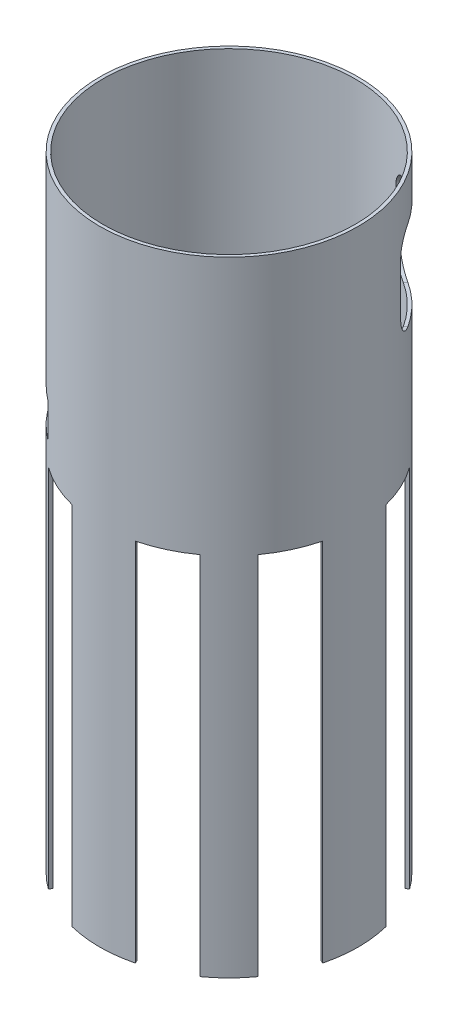
SolidWorks part; units mm, degrees
ref_plane "Front Plane" through (0, 0, 0) normal (0, 0, 1) x (1, 0, 0)
ref_plane "Top Plane" through (0, 0, 0) normal (0, 1, 0) x (1, 0, 0)
ref_plane "Right Plane" through (0, 0, 0) normal (1, 0, 0) x (0, 0, -1)
sketch "Sketch1" plane through (0, 63, 0) normal (0, 1, 0) x (1, 0, 0)
  circle A0 centre (0, 0) radius 40
  circle A1 centre (0, 0) radius 39
  dimension "D1" = 78
  dimension "D2" = 80
extrude "Boss-Extrude1" add sketch "Sketch1" along normal blind 193
sketch "Sketch8" plane through (24.1692, 0, -24.1692) normal (-0.7071, 0, 0.7071) x (0.7071, 0, 0.7071)
  circle A0 centre (0, 68) radius 1.6
sketch "Sketch9" plane through (0, 0, 0) normal (0, 0, 1) x (1, 0, 0)
  line L0 (0, 256) -> (0, 212.8531) construction
  line L1 (40, 256) -> (-40, 256) construction
  line L3 (-10, 234) -> (10, 234)
  line L4 (-10, 234) -> (-10, 214)
  line L5 (-10, 214) -> (10, 214)
  line L6 (10, 234) -> (10, 214)
  line L7 (-10, 234) -> (10, 214) construction
  line L8 (-10, 214) -> (10, 234) construction
  point P5 (0, 224)
  dimension "D1" = 20
  dimension "D2" = 20
  dimension "D3" = 22
sketch "Sketch11" plane through (0, 256, 0) normal (0, 1, 0) x (1, 0, 0)
  line L0 (-24.0172, 11.1994) -> (0, 0) construction
  line L6 (16.4552, 17.5418) -> (2.8606, 23.8811)
  line L22 (2.8606, 23.8811) -> (12.7622, 45.1151)
  line L23 (12.7622, 45.1151) -> (26.3568, 38.7759)
  line L24 (26.3568, 38.7759) -> (16.4552, 17.5418)
  line L25 (-17.5418, 16.4552) -> (-23.8811, 2.8606)
  line L26 (0, 0) -> (-24.0172, -11.1994) construction
  line L27 (-23.8811, 2.8606) -> (-45.1151, 12.7622)
  line L44 (-45.1151, 12.7622) -> (-38.7759, 26.3568)
  line L45 (-38.7759, 26.3568) -> (-17.5418, 16.4552)
  line L46 (17.5418, -16.4552) -> (23.8811, -2.8606)
  line L47 (23.8811, -2.8606) -> (45.1151, -12.7622)
  line L48 (45.1151, -12.7622) -> (38.7759, -26.3568)
  line L49 (38.7759, -26.3568) -> (17.5418, -16.4552)
  line L50 (-16.4552, -17.5418) -> (-2.8606, -23.8811)
  line L51 (-2.8606, -23.8811) -> (-12.7622, -45.1151)
  line L52 (-12.7622, -45.1151) -> (-26.3568, -38.7759)
  line L53 (-26.3568, -38.7759) -> (-16.4552, -17.5418)
  line L54 (-43.6206, -12.0653) -> (-21.5665, -1.7813)
  line L55 (-21.5665, -1.7813) -> (-15.2272, -15.3759)
  line L56 (-15.2272, -15.3759) -> (-37.2813, -25.6599)
  line L57 (-37.2813, -25.6599) -> (-43.6206, -12.0653)
  line L58 (-12.0653, 43.6206) -> (-1.7813, 21.5665)
  line L59 (-1.7813, 21.5665) -> (-15.3759, 15.2272)
  line L60 (-15.3759, 15.2272) -> (-25.6599, 37.2813)
  line L61 (-25.6599, 37.2813) -> (-12.0653, 43.6206)
  line L62 (43.6206, 12.0653) -> (21.5665, 1.7813)
  line L63 (21.5665, 1.7813) -> (15.2272, 15.3759)
  line L64 (15.2272, 15.3759) -> (37.2813, 25.6599)
  line L65 (37.2813, 25.6599) -> (43.6206, 12.0653)
  line L66 (12.0653, -43.6206) -> (1.7813, -21.5665)
  line L67 (1.7813, -21.5665) -> (15.3759, -15.2272)
  line L68 (15.3759, -15.2272) -> (25.6599, -37.2813)
  line L69 (25.6599, -37.2813) -> (12.0653, -43.6206)
  point P5 (-24.6066, 4.854)
  point P6 (-19.5352, 15.7297)
  point P23 (0, 0)
  point P25 (-22.292, -3.7747)
  point P26 (-17.2206, -14.6504)
  point P43 (0, 0)
  point P69 (-24.6511, 9.8399)
  point P70 (-3.5493, 0)
  point P71 (-24.6511, -9.8399)
extrude "Cut-Extrude3" cut sketch "Sketch11" against normal blind 150 from offset 80 offset against normal yes
ref_plane "Plane2" through (-28.2843, 0, -28.2843) normal (-0.7071, 0, -0.7071) x (-0.7071, 0, 0.7071)
ref_plane "Plane3"
sketch "Sketch15" plane through (0, 0, 0) normal (0, 0, 1) x (1, 0, 0)
  line L52 (-12.2404, 248.0147) -> (-13.4404, 246.8147)
  line L53 (-13.4404, 246.8147) -> (-13.4404, 223.8147)
  line L54 (-13.4404, 223.8147) -> (-12.2404, 222.6147)
  line L55 (-12.2404, 222.6147) -> (10.7596, 222.6147)
  line L56 (10.7596, 222.6147) -> (11.9596, 223.8147)
  line L57 (11.9596, 223.8147) -> (11.9596, 246.8147)
  line L58 (11.9596, 246.8147) -> (10.7596, 248.0147)
  line L59 (10.7596, 248.0147) -> (-12.2404, 248.0147)
sketch "Sketch16" plane through (0, 256, 0) normal (0, 1, 0) x (1, 0, 0)
  circle A0 centre (0, 0) radius 40
ref_plane "Plane4" through (30.5428, 0, -30.5428) normal (0.7071, 0, -0.7071) x (-0.7044, 0.0877, -0.7044)
sketch "Sketch20" plane through (30.5428, 0, -30.5428) normal (0.7071, 0, -0.7071) x (-0.7044, 0.0877, -0.7044)
  line L76 (7.0514, 237.4766) -> (5.5905, 220.8807)
  line L77 (29.5758, 240.9849) -> (12.98, 242.4458)
  line L78 (33.0842, 218.4605) -> (34.5451, 235.0563)
  line L79 (10.5598, 214.9522) -> (27.1556, 213.4912)
  line L80 (7.0514, 237.4766) -> (5.5905, 220.8807)
  line L81 (29.5758, 240.9849) -> (12.98, 242.4458)
  line L82 (33.0842, 218.4605) -> (34.5451, 235.0563)
  line L83 (10.5598, 214.9522) -> (27.1556, 213.4912)
  arc A31 (5.5905, 220.8807) -> (10.5598, 214.9522) centre (11.0394, 220.4011) ccw
  arc A32 (12.98, 242.4458) -> (7.0514, 237.4766) centre (12.5004, 236.9969) ccw
  arc A33 (34.5451, 235.0563) -> (29.5758, 240.9849) centre (29.0962, 235.536) ccw
  arc A34 (27.1556, 213.4912) -> (33.0842, 218.4605) centre (27.6353, 218.9402) ccw
  arc A35 (5.5905, 220.8807) -> (10.5598, 214.9522) centre (11.0394, 220.4011) ccw
  arc A36 (12.98, 242.4458) -> (7.0514, 237.4766) centre (12.5004, 236.9969) ccw
  arc A37 (34.5451, 235.0563) -> (29.5758, 240.9849) centre (29.0962, 235.536) ccw
  arc A38 (27.1556, 213.4912) -> (33.0842, 218.4605) centre (27.6353, 218.9402) ccw
  dimension "D1" = 2
extrude "Cut-Extrude4" cut sketch "Sketch20" against normal blind 35
ref_plane "Plane5" through (24.1692, 0, -24.1692) normal (-0.7071, 0, 0.7071) x (0.7071, 0, 0.7071)
sketch "Sketch22" plane through (24.1692, 0, -24.1692) normal (-0.7071, 0, 0.7071) x (0.7071, 0, 0.7071)
  circle A0 centre (0, 68) radius 1.7
  dimension "D1" = 3.4
extrude "Cut-Extrude5" cut sketch "Sketch22" against normal blind 5.3
pattern_circular "CirPattern1" count 4 over 360 about axis through (0, 0, 0) along (0, 1, 0) of "Cut-Extrude5"
ref_plane "Plane6" through (-28.0563, 0, 20.3841) normal (0.809, 0, -0.5878) x (-0.5878, 0, -0.809)
sketch "Sketch24" plane through (-28.0563, 0, 20.3841) normal (0.809, 0, -0.5878) x (-0.5878, 0, -0.809)
  line L0 (-11.7045, 182.803) -> (19.5277, 182.803)
  line L2 (-11.7045, 182.803) -> (-11.7045, 193.4587)
  line L3 (-11.7045, 193.4587) -> (19.5277, 193.4587)
  line L4 (19.5277, 182.803) -> (19.5277, 193.4587)
extrude "Cut-Extrude6" cut sketch "Sketch24" against normal blind 13.3
